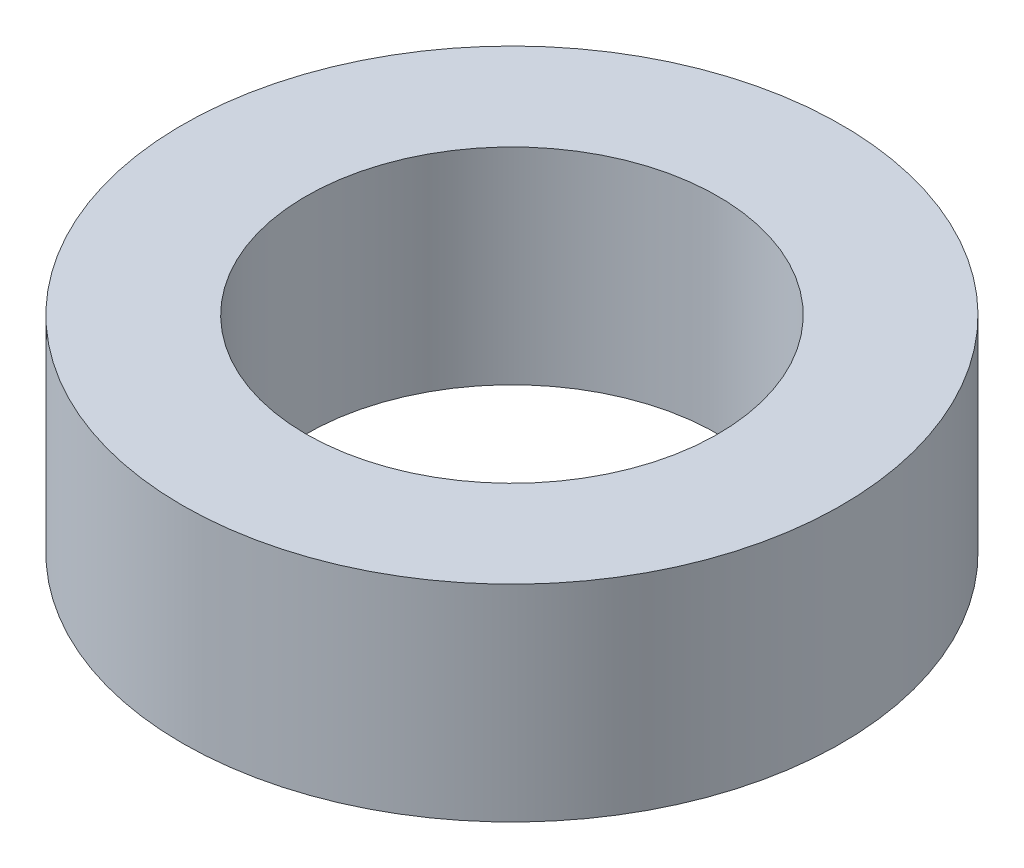
SolidWorks part; units mm, degrees
material "ABS PC"
ref_plane "Front Plane" through (0, 0, 0) normal (0, 0, 1) x (1, 0, 0)
ref_plane "Top Plane" through (0, 0, 0) normal (0, 1, 0) x (1, 0, 0)
ref_plane "Right Plane" through (0, 0, 0) normal (1, 0, 0) x (0, 0, -1)
sketch "Sketch1" plane through (0, 0, 0) normal (0, 1, 0) x (1, 0, 0)
  circle A0 centre (0, 0) radius 3.175
  circle A1 centre (0, 0) radius 5.08
extrude "Boss-Extrude1" add sketch "Sketch1" along normal blind 3.175
